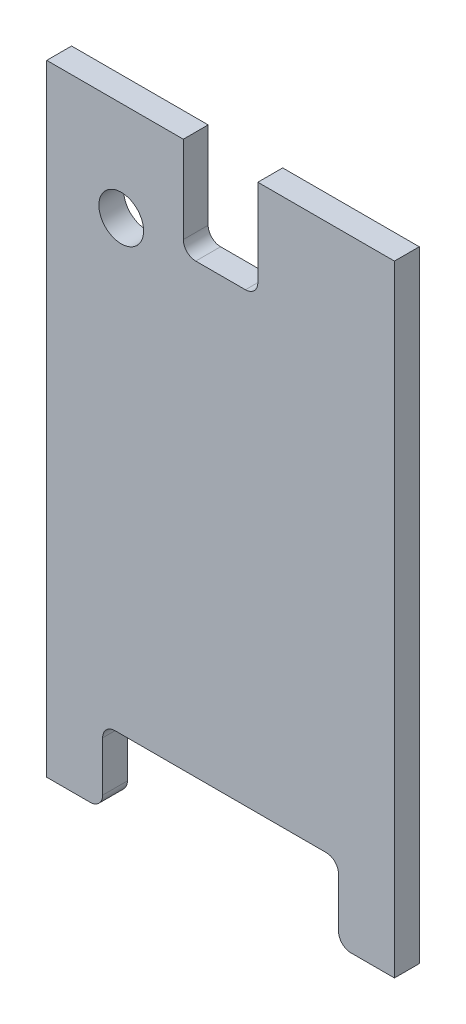
SolidWorks part; units mm, degrees
material "Balsa"
ref_plane "Front Plane" through (0, 0, 0) normal (0, 0, 1) x (1, 0, 0)
ref_plane "Top Plane" through (0, 0, 0) normal (0, 1, 0) x (1, 0, 0)
ref_plane "Right Plane" through (0, 0, 0) normal (1, 0, 0) x (0, 0, -1)
sketch "Sketch1" plane through (0, 0, 0) normal (0, 0, 1) x (1, 0, 0)
  line L0 (103.9728, 346.7736) -> (173.8228, 346.7736)
  line L1 (-3.9772, 346.7736) -> (65.8728, 346.7736)
  line L2 (-3.9772, 346.7736) -> (-3.9772, 35.6236)
  line L3 (2.3728, 29.2736) -> (18.2478, 29.2736)
  line L4 (173.8228, 346.7736) -> (173.8228, 35.6236)
  line L6 (65.8728, 346.7736) -> (65.8728, 302.3236)
  line L7 (72.2228, 295.9736) -> (97.6228, 295.9736)
  line L8 (103.9728, 346.7736) -> (103.9728, 302.3236)
  line L9 (151.5978, 29.2736) -> (161.1228, 29.2736)
  line L11 (24.5978, 35.6236) -> (24.5978, 61.0236)
  line L12 (30.9478, 67.3736) -> (138.8978, 67.3736)
  line L13 (145.2478, 35.6236) -> (145.2478, 61.0236)
  line L14 (-3.9772, 35.6236) -> (-3.9772, 29.2736)
  line L15 (-3.9772, 29.2736) -> (2.3728, 29.2736)
  line L16 (173.8228, 35.6236) -> (173.8228, 29.2736)
  line L17 (173.8228, 29.2736) -> (161.1228, 29.2736)
  arc A2 (18.2478, 29.2736) -> (24.5978, 35.6236) centre (18.2478, 35.6236) ccw
  arc A3 (24.5978, 61.0236) -> (30.9478, 67.3736) centre (30.9478, 61.0236) cw
  arc A4 (138.8978, 67.3736) -> (145.2478, 61.0236) centre (138.8978, 61.0236) cw
  arc A5 (151.5978, 29.2736) -> (145.2478, 35.6236) centre (151.5978, 35.6236) cw
  arc A6 (97.6228, 295.9736) -> (103.9728, 302.3236) centre (97.6228, 302.3236) ccw
  arc A7 (65.8728, 302.3236) -> (72.2228, 295.9736) centre (72.2228, 302.3236) ccw
  circle A8 centre (34.1228, 295.9736) radius 11.43
  point P14 (173.8228, 29.2736)
  point P17 (-3.9772, 29.2736)
  point P22 (24.5978, 67.3736)
  point P25 (145.2478, 67.3736)
  point P28 (145.2478, 29.2736)
  point P31 (103.9728, 295.9736)
  point P34 (65.8728, 295.9736)
  dimension "D9" = 22.86
  dimension "D1" = 317.5
  dimension "D2" = 177.8
  dimension "D3" = 38.1
  dimension "D4" = 50.8
  dimension "D5" = 69.85
  dimension "D6" = 120.65
  dimension "D7" = 28.575
  dimension "D8" = 38.1
  dimension "D10" = 38.1
  dimension "D11" = 50.8
extrude "Boss-Extrude2" add sketch "Sketch1" along normal blind 12.7 contours L0 L4 L16 L17 L9 A5 L13 A4 L12 A3 L11 A2 L3 L15 L14 L2 L1 L6 A7 L7 A6 L8
